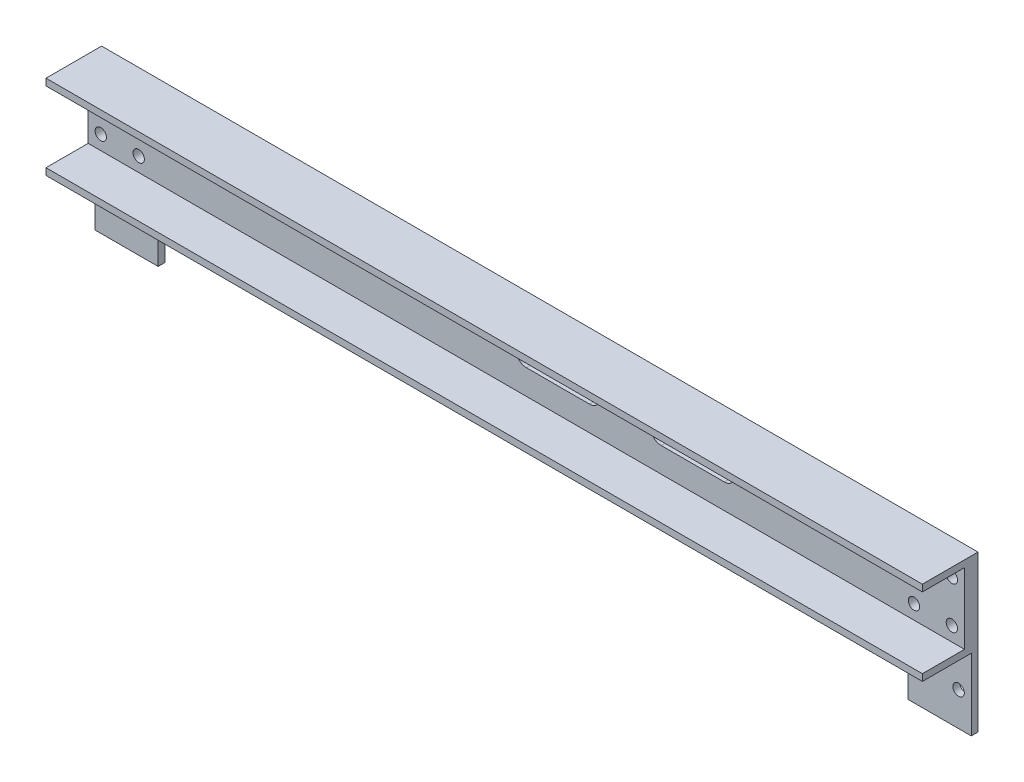
SolidWorks part; units mm, degrees
ref_plane "Front Plane" through (0, 0, 0) normal (0, 0, 1) x (1, 0, 0)
ref_plane "Top Plane" through (0, 0, 0) normal (0, 1, 0) x (1, 0, 0)
ref_plane "Right Plane" through (0, 0, 0) normal (1, 0, 0) x (0, 0, -1)
sketch "Sketch1" plane through (0, 0, 0) normal (0, 0, 1) x (1, 0, 0)
  line L1 (-445, -50) -> (445, -50)
  line L2 (-520, -50) -> (-520, 50)
  line L3 (-520, 50) -> (520, 50)
  line L4 (520, -50) -> (520, 50)
  line L5 (-520, -50) -> (520, 50) construction
  line L6 (-520, 50) -> (520, -50) construction
  line L8 (-520, -50) -> (-520, -135)
  line L9 (-520, -135) -> (-445, -135)
  line L10 (-445, -50) -> (-445, -135)
  line L12 (520, -50) -> (520, -135)
  line L13 (520, -135) -> (445, -135)
  line L14 (445, -50) -> (445, -135)
  point P0 (0, 0)
  dimension "D1" = 100
  dimension "D2" = 1040
  dimension "D3" = 85
  dimension "D4" = 75
  dimension "D5" = 85
  dimension "D6" = 75
  dimension "D7" = 890
  dimension "D8" = 85
  dimension "D9" = 85
extrude "Boss-Extrude1" add sketch "Sketch1" along normal blind 8
sketch "Sketch2" plane through (0, 0, 8) normal (0, 0, 1) x (1, 0, 0)
  line L1 (-520, -50) -> (520, -50)
  line L2 (-520, -50) -> (-520, 50)
  line L3 (-520, 50) -> (520, 50)
  line L4 (520, -50) -> (520, 50)
  line L5 (-520, -50) -> (520, 50) construction
  line L6 (-520, 50) -> (520, -50) construction
  point P0 (0, 0)
extrude "Boss-Extrude2" add sketch "Sketch2" along normal blind 8
sketch "Sketch3" plane through (0, 0, 16) normal (0, 0, 1) x (1, 0, 0)
  line L1 (0, 0) -> (75, 0) construction
  line L2 (0, 12.5) -> (75, 12.5)
  line L3 (0, -12.5) -> (75, -12.5)
  line L4 (160, 0) -> (235, 0) construction
  line L5 (160, 12.5) -> (235, 12.5)
  line L6 (160, -12.5) -> (235, -12.5)
  arc A0 (0, 12.5) -> (0, -12.5) centre (0, 0) ccw
  arc A1 (75, -12.5) -> (75, 12.5) centre (75, 0) ccw
  arc A2 (160, 12.5) -> (160, -12.5) centre (160, 0) ccw
  arc A3 (235, -12.5) -> (235, 12.5) centre (235, 0) ccw
  point P0 (197.5, 0)
  point P1 (37.5, 0)
  point P9 (-12.5, 0)
  point P10 (87.5, 0)
  point P13 (197.5, 0)
  dimension "D1" = 100
  dimension "D2" = 25
  dimension "D3" = 160
extrude "Cut-Extrude1" cut sketch "Sketch3" against normal through all both and the other way through all
sketch "Sketch4" plane through (0, 0, 16) normal (0, 0, 1) x (1, 0, 0)
  line L2 (520, 42) -> (-520, 42)
  line L3 (520, 42) -> (-520, 42)
  line L4 (-520, -42) -> (-520, -50)
  line L5 (-520, -42) -> (520, -42)
  line L6 (-520, -42) -> (520, -42)
  line L7 (520, 42) -> (520, 50)
  line L10 (520, -50) -> (520, 50)
  line L11 (520, 50) -> (-520, 50)
  line L12 (-520, 50) -> (-520, -50)
  line L13 (-520, -50) -> (520, -50)
  line L14 (520, -50) -> (520, -42)
  line L15 (520, 50) -> (-520, 50)
  line L16 (-520, 50) -> (-520, 42)
  line L17 (-520, -50) -> (520, -50)
  dimension "D1" = 8
  dimension "D2" = 8
  dimension "D3" = 0
extrude "Boss-Extrude3" add sketch "Sketch4" along normal blind 50
hole_wizard "Ø12.0mm Dowel Hole1" positions "Sketch6" profile "Sketch7" hole size "Ø12.0" standard "ISO" end condition up to next
sketch "Sketch6" plane through (0, 0, 16) normal (0, 0, 1) x (1, 0, 0)
  line L0 (-520, 42) -> (-520, -42) construction
  line L1 (520, -42) -> (520, 42) construction
  line L2 (-520, -135) -> (-445, -135) construction
  line L3 (520, 50) -> (-520, 50) construction
  point P0 (-460, 25)
  point P3 (-505, 25)
  point P5 (-505, -25)
  point P7 (-460, -25)
  point P9 (-460, -95)
  point P11 (-505, -95)
  point P13 (460, -95)
  point P15 (505, -95)
  point P17 (505, -25)
  point P19 (460, -25)
  point P21 (460, 25)
  point P23 (505, 25)
  point P26 (0, 0)
  point P27 (0, 0)
  point P28 (0, 0)
  point P29 (0, 0)
  point P30 (0, 0)
  point P31 (0, 0)
  point P32 (0, 0)
  point P33 (0, 0)
  dimension "D1" = 15
  dimension "D2" = 45
  dimension "D3" = 15
  dimension "D4" = 45
  dimension "D5" = 40
  dimension "D6" = 70
  dimension "D7" = 50
  dimension "D8" = 25
sketch "Sketch7" plane through (-460, 25, 16) normal (1, 0, 0) x (0, -1, 0)
  line L0 (0, 0) -> (0, 16)
  line L1 (0, 16) -> (6.75, 16)
  line L2 (6.75, 16) -> (6.75, 0)
  line L5 (6.75, 0) -> (0, 0)
  line L11 (0, -6.35) -> (0, 107.95) construction
  dimension "Thru Hole Dia." = 13.5
  dimension "Thru Hole Depth" = 16
